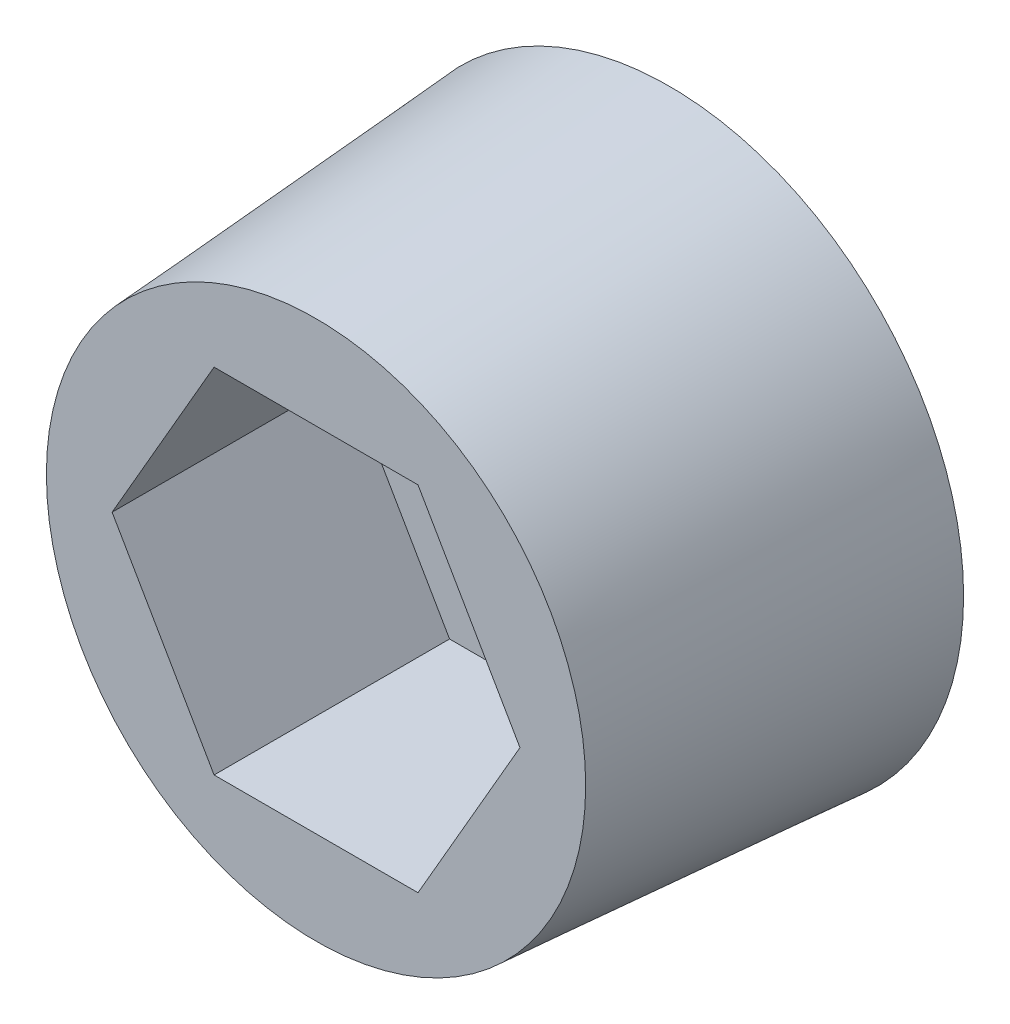
SolidWorks part; units mm, degrees
ref_plane "Front Plane" through (0, 0, 0) normal (0, 0, 1) x (1, 0, 0)
ref_plane "Top Plane" through (0, 0, 0) normal (0, 1, 0) x (1, 0, 0)
ref_plane "Right Plane" through (0, 0, 0) normal (1, 0, 0) x (0, 0, -1)
sketch "Sketch1" plane through (0, 0, 0) normal (0, 0, 1) x (1, 0, 0)
  circle A0 centre (0, 0) radius 5
  dimension "D1" = 10
extrude "Boss-Extrude1" add sketch "Sketch1" along normal blind 6 draft 4
sketch "Sketch2" plane through (0, 0, 6) normal (0, 0, 1) x (1, 0, 0)
  line L1 (1.7321, 3) -> (-1.7321, 3)
  line L2 (-1.7321, 3) -> (-3.4641, 0)
  line L3 (-3.4641, 0) -> (-1.7321, -3)
  line L4 (-1.7321, -3) -> (1.7321, -3)
  line L5 (1.7321, -3) -> (3.4641, 0)
  line L6 (3.4641, 0) -> (1.7321, 3)
  circle A0 centre (0, 0) radius 3 construction
  dimension "D1" = 6
extrude "Cut-Extrude1" cut sketch "Sketch2" against normal blind 4
sketch "Sketch4" plane through (0, 0, 2) normal (0, 0, 1) x (1, 0, 0)
  circle A0 centre (0, 0) radius 1.65
  dimension "D1" = 3.3
extrude "Cut-Extrude2" cut sketch "Sketch4" against normal through all
